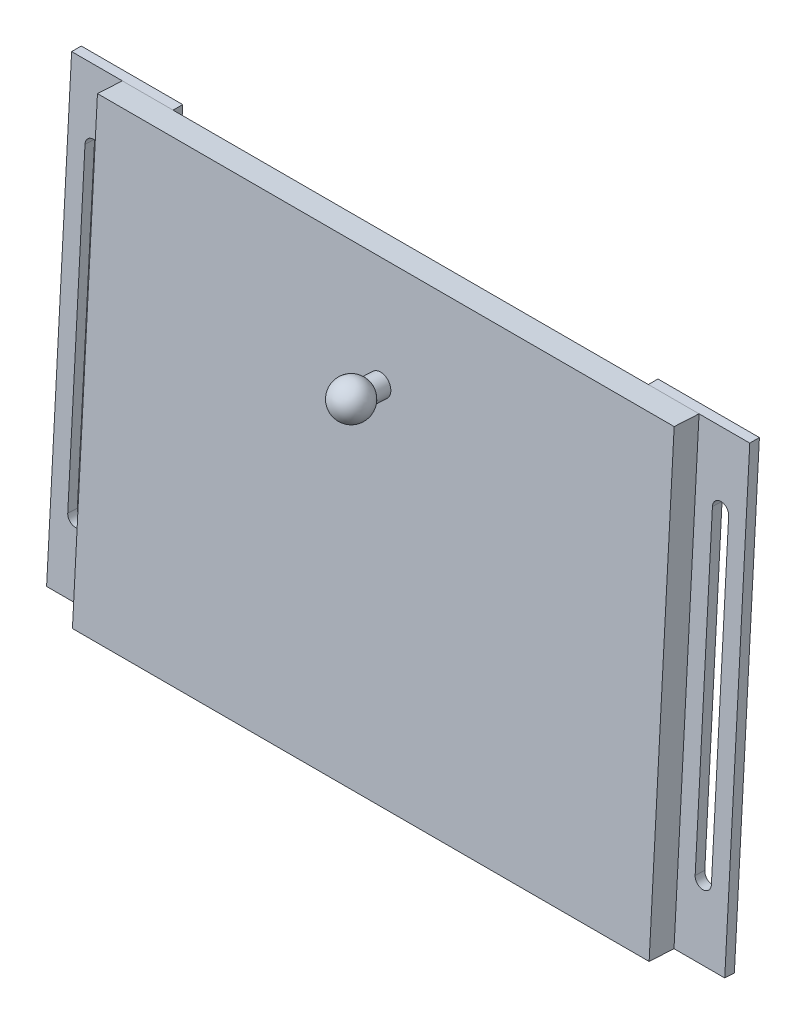
SolidWorks part; units mm, degrees
ref_plane "Plan de face" through (0, 0, 0) normal (0, 0, 1) x (1, 0, 0)
ref_plane "Plan de dessus" through (0, 0, 0) normal (0, 1, 0) x (1, 0, 0)
ref_plane "Plan de droite" through (0, 0, 0) normal (1, 0, 0) x (0, 0, -1)
sketch "Esquisse1" plane through (0, 0, 0) normal (1, 0, 0) x (0, 0, -1)
  line L0 (0.0983, 46.0655) -> (5.005, 45.7929)
  line L1 (5.005, 45.7929) -> (0.0681, -43.0701)
  line L2 (0.0681, -43.0701) -> (-4.8386, -42.7975)
  line L3 (-4.8386, -42.7975) -> (0.0983, 46.0655)
  dimension "D1" = 89
extrude "Boss.-Extru.1" add sketch "Esquisse1" along normal blind 113.7
sketch "Esquisse4" plane through (0, 0, 0) normal (-1, 0, 0) x (0, 0, 1)
  line L0 (-5.005, 45.7929) -> (-6.905, 45.7929)
  line L1 (-6.905, 45.7929) -> (-1.9681, -43.1755)
  line L2 (-1.9681, -43.1755) -> (-0.0681, -43.0701)
  line L7 (4.8386, -42.7975) -> (-0.0983, 46.0655)
  line L8 (-0.0983, 46.0655) -> (-5.005, 45.7929)
  line L9 (-5.005, 45.7929) -> (-0.0681, -43.0701)
  line L10 (-0.0681, -43.0701) -> (4.8386, -42.7975)
  line L13 (-5.005, 45.7929) -> (-0.0681, -43.0701)
  dimension "D1" = 1.9
  dimension "D2" = 1.9
  dimension "D3" = 0
extrude "Boss.-Extru.2" add sketch "Esquisse4" along normal mid plane 20
ref_plane "Plan1" through (50, 0, 0) normal (1, 0, 0) x (0, 0, -1)
sketch "Esquisse5" plane through (0, -0.2414, -4.3506) normal (0, -0.0554, -0.9985) x (-1, 0, 0)
  line L0 (0, 46.1051) -> (10, 46.1051) construction
  line L1 (10, 46.1051) -> (-10, 46.1051) construction
  line L2 (10, 46.1051) -> (5, 46.1051) construction
  line L3 (5, 46.1051) -> (5, -43.0002) construction
  line L4 (10, -43.0002) -> (-10, -43.0002) construction
  line L5 (5, -29.1381) -> (5, 32.243) construction
  line L6 (3.4, -29.1381) -> (3.4, 32.243)
  line L7 (6.6, -29.1381) -> (6.6, 32.243)
  arc A0 (3.4, -29.1381) -> (6.6, -29.1381) centre (5, -29.1381) ccw
  arc A1 (6.6, 32.243) -> (3.4, 32.243) centre (5, 32.243) ccw
  point P11 (5, 1.5525)
  dimension "D1" = 3.2
extrude "Enlèv. mat.-Extru.1" cut sketch "Esquisse5" against normal blind 10
sketch "Esquisse7" plane through (0, 0.1363, 2.4534) normal (0, 0.0555, 0.9985) x (1, 0, 0)
  line L0 (56.85, 46) -> (56.85, -43) construction
  line L1 (113.7, 46) -> (0, 46) construction
  line L2 (113.7, -43) -> (0, -43) construction
  circle A0 centre (56.8495, 25.2345) radius 2.1354
  dimension "D1" = 0.001
extrude "Boss.-Extru.3" add sketch "Esquisse7" along normal blind 8
ref_plane "Plan2" through (56.85, 0, 0) normal (1, 0, 0) x (0, 0, -1)
sketch "Esquisse8" plane through (56.85, 0, 0) normal (1, 0, 0) x (0, 0, -1)
  line L0 (-6.4066, 29.3095) -> (-7.0635, 22.1663)
  arc A1 (-6.4066, 29.3095) -> (-7.0635, 22.1663) centre (-6.735, 25.7379) ccw
revolve "Révolution4" add sketch "Esquisse8" angle 360 about L0
mirror "Symétrie1" about plane through (56.85, 0, 0) normal (1, 0, 0) of "Enlèv. mat.-Extru.1", "Boss.-Extru.2"
